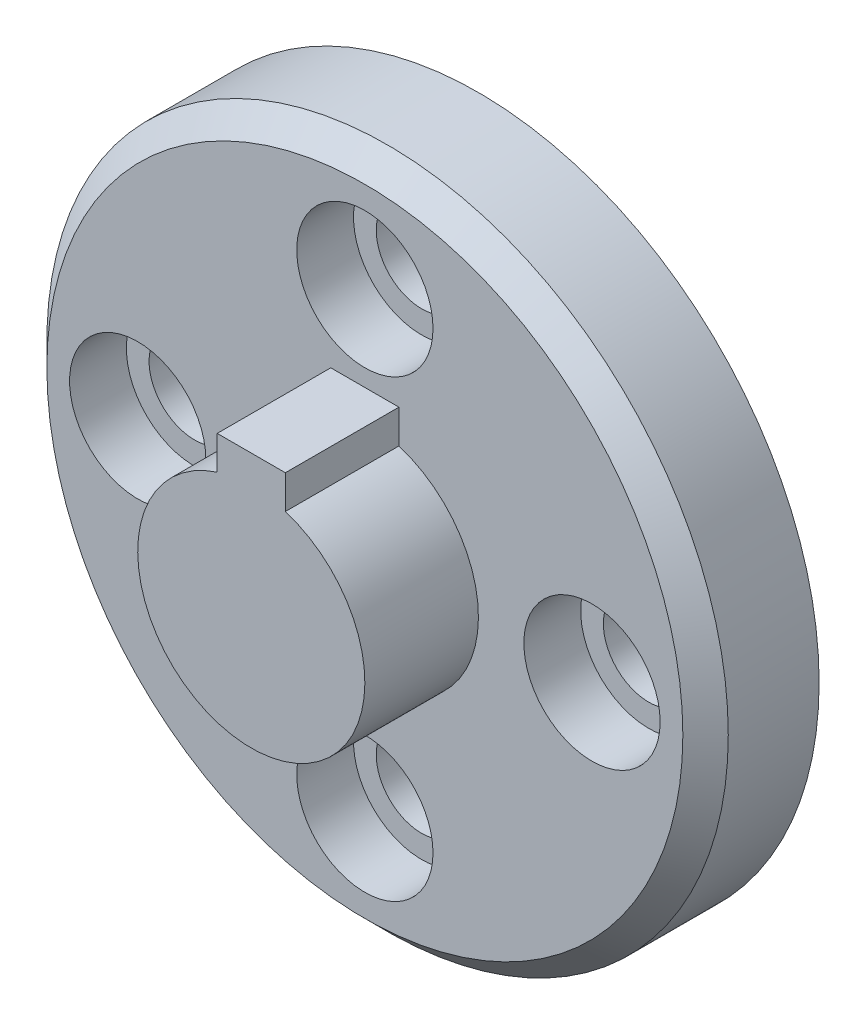
SolidWorks part; units mm, degrees
ref_plane "Front Plane" through (0, 0, 0) normal (0, 0, 1) x (1, 0, 0)
ref_plane "Top Plane" through (0, 0, 0) normal (0, 1, 0) x (1, 0, 0)
ref_plane "Right Plane" through (0, 0, 0) normal (1, 0, 0) x (0, 0, -1)
sketch "Sketch1" plane through (0, 0, 0) normal (0, 0, 1) x (1, 0, 0)
  circle A0 centre (0, 0) radius 15
  circle A1 centre (0, 0) radius 10 construction
  circle A2 centre (0, 10) radius 2
  circle A3 centre (10, 0) radius 2
  circle A4 centre (0, -10) radius 2
  circle A5 centre (-10, 0) radius 2
  point P15 (0, 0)
  dimension "D1" = 20
  dimension "D2" = 4
  dimension "D3" = 4
  dimension "D4" = 30
extrude "Boss-Extrude1" add sketch "Sketch1" along normal blind 5
sketch "Sketch2" plane through (0, 0, 5) normal (0, 0, 1) x (1, 0, 0)
  line L0 (-1.5, 4.7697) -> (-1.5, 3.75) construction
  line L1 (-1.5, 6.25) -> (1.5, 6.25)
  line L2 (-1.5, 6.25) -> (-1.5, 4.7697)
  line L4 (1.5, 6.25) -> (1.5, 4.7697)
  line L5 (-1.5, 6.25) -> (1.5, 3.75) construction
  line L6 (-1.5, 3.75) -> (1.5, 6.25) construction
  line L7 (-1.5, 3.75) -> (1.5, 3.75) construction
  line L8 (1.5, 3.75) -> (1.5, 4.7697) construction
  arc A0 (-1.5, 4.7697) -> (1.5, 4.7697) centre (0, 0) ccw
  point P3 (0, 5)
  dimension "D1" = 3
  dimension "D3" = 10
  dimension "D2" = 2.5
extrude "Boss-Extrude2" add sketch "Sketch2" along normal blind 5
sketch "Sketch3" plane through (0, 0, 5) normal (0, 0, 1) x (1, 0, 0)
  circle A1 centre (0, 10) radius 3
  circle A2 centre (-10, 0) radius 3
  circle A3 centre (-10, 0) radius 3
  circle A4 centre (10, 0) radius 3
  circle A5 centre (0, -10) radius 3
  point P12 (0, 0)
  dimension "D1" = 1
  dimension "D2" = 4
extrude "Cut-Extrude1" cut sketch "Sketch3" against normal blind 2.5
chamfer "Chamfer1" distance 1 angle 45 1 edges at (15, 0, 5)
